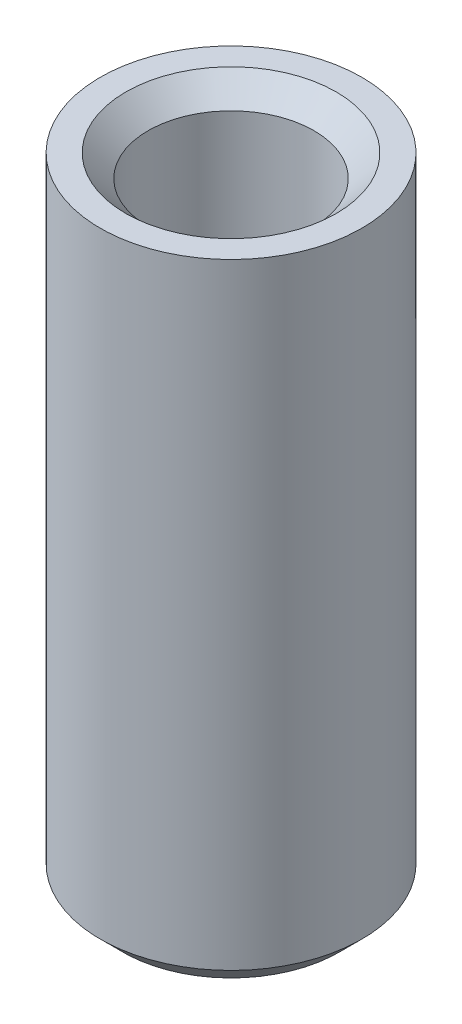
SolidWorks part; units mm, degrees
material "Custom Plastic"
ref_plane "Front Plane" through (0, 0, 0) normal (0, 0, 1) x (1, 0, 0)
ref_plane "Top Plane" through (0, 0, 0) normal (0, 1, 0) x (1, 0, 0)
ref_plane "Right Plane" through (0, 0, 0) normal (1, 0, 0) x (0, 0, -1)
sketch "Sketch1" plane through (0, 0, 0) normal (0, 0, 1) x (1, 0, 0)
  line L0 (0, 0) -> (0, 48.5947) construction
  line L1 (-2.6, 0) -> (-3.4, 0)
  line L2 (-3.4, 0) -> (-4.1, 0.7)
  line L3 (-4.1, 0.7) -> (-4.1, 20)
  line L4 (-4.1, 20) -> (-3.3, 20)
  line L5 (-3.3, 20) -> (-2.6, 19.3)
  line L6 (-2.6, 19.3) -> (-2.6, 0)
  dimension "D1" = 45
  dimension "D2" = 8.2
  dimension "D3" = 0.8
  dimension "D4" = 5.2
  dimension "D5" = 20
revolve "Revolve1" add sketch "Sketch1" angle 360 about L0
